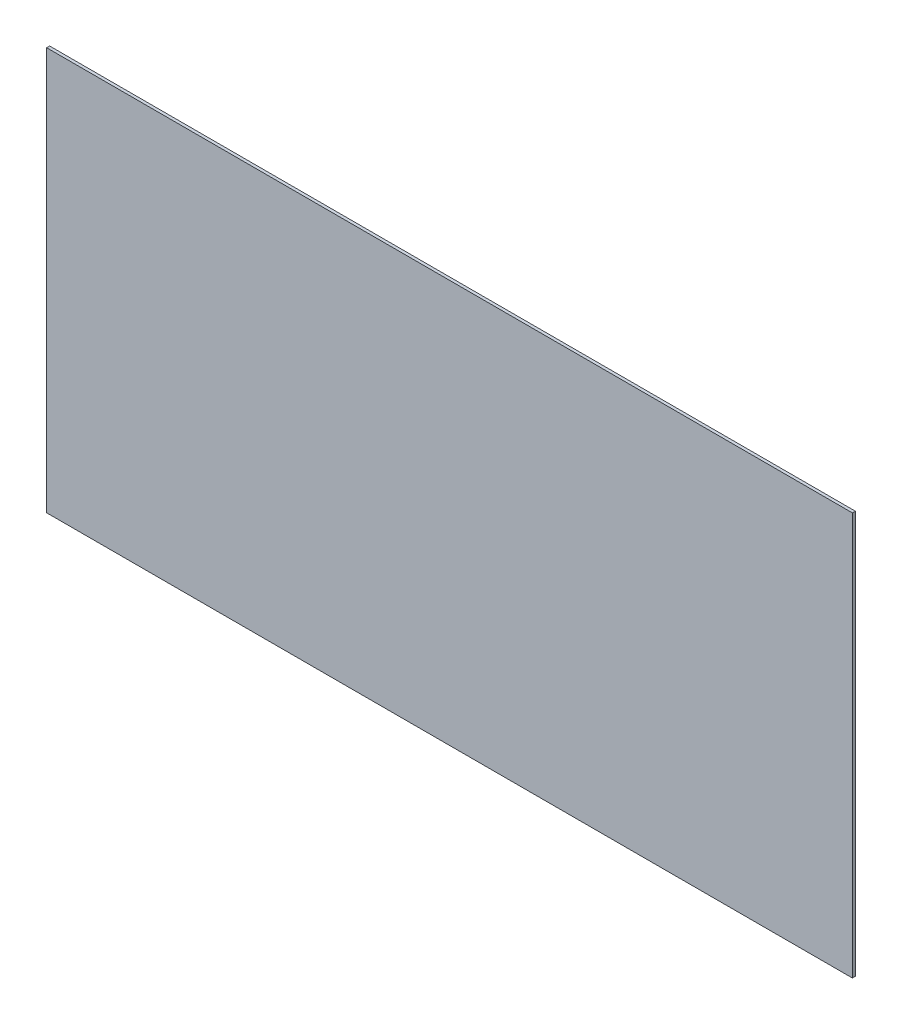
SolidWorks part; units mm, degrees
ref_plane "Front Plane" through (0, 0, 0) normal (0, 0, 1) x (1, 0, 0)
ref_plane "Top Plane" through (0, 0, 0) normal (0, 1, 0) x (1, 0, 0)
ref_plane "Right Plane" through (0, 0, 0) normal (1, 0, 0) x (0, 0, -1)
sketch "Sketch1" plane through (0, 0, 0) normal (0, 0, 1) x (1, 0, 0)
  line L1 (0, 5) -> (20, 5)
  line L2 (0, 5) -> (0, -5)
  line L3 (0, -5) -> (20, -5)
  line L4 (20, 5) -> (20, -5)
  point P6 (0, 0)
  dimension "D1" = 10
  dimension "D2" = 20
extrude "Boss-Extrude1" add sketch "Sketch1" along normal blind 0.0737
